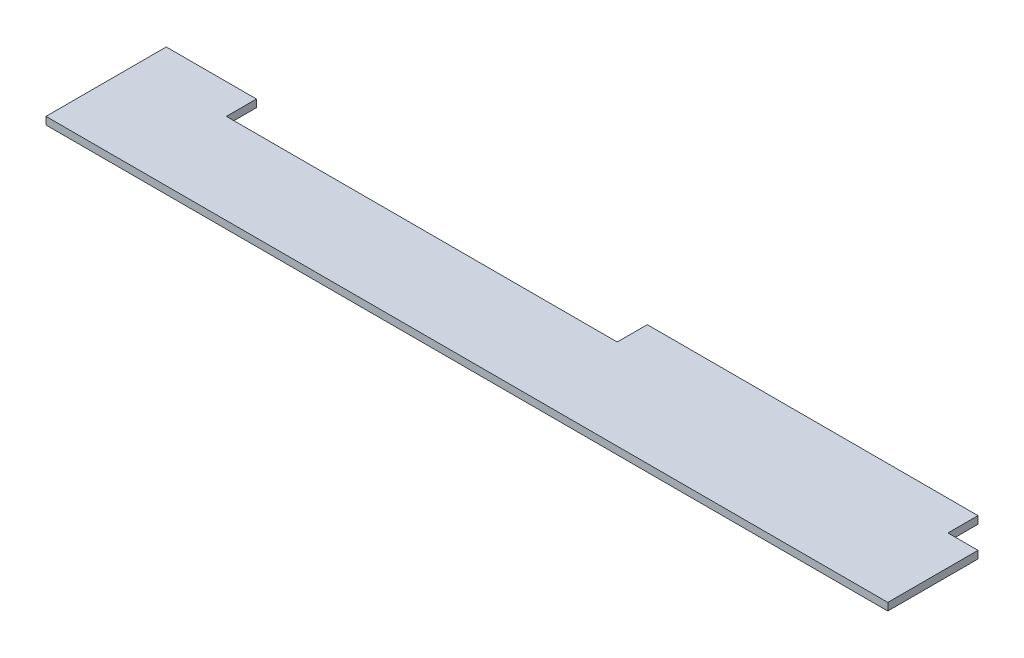
SolidWorks part; units mm, degrees
ref_plane "Front Plane" through (0, 0, 0) normal (0, 0, 1) x (1, 0, 0)
ref_plane "Top Plane" through (0, 0, 0) normal (0, 1, 0) x (1, 0, 0)
ref_plane "Right Plane" through (0, 0, 0) normal (1, 0, 0) x (0, 0, -1)
sketch "Sketch1" plane through (0, 0, 0) normal (0, 1, 0) x (1, 0, 0)
  line L0 (0, 0) -> (0, 25.4)
  line L1 (0, 25.4) -> (279.4, 25.4)
  line L2 (279.4, 25.4) -> (279.4, 0)
  line L3 (279.4, 0) -> (304.8, 0)
  line L4 (304.8, 0) -> (304.8, -76.2)
  line L5 (304.8, -76.2) -> (-406.4, -76.2)
  line L6 (-406.4, -76.2) -> (-406.4, 25.4)
  line L7 (-330.2, 0) -> (0, 0)
  line L9 (-406.4, 25.4) -> (-330.2, 25.4)
  line L10 (-330.2, 25.4) -> (-330.2, 0)
  point P10 (0, 0)
  point P13 (-406.4, 2.8436)
  point P14 (-406.4, 24.5716)
  dimension "D1" = 25.4
  dimension "D2" = 279.4
  dimension "D3" = 76.2
  dimension "D4" = 711.2
  dimension "D5" = 76.2
extrude "Boss-Extrude1" add sketch "Sketch1" along normal blind 6.35
